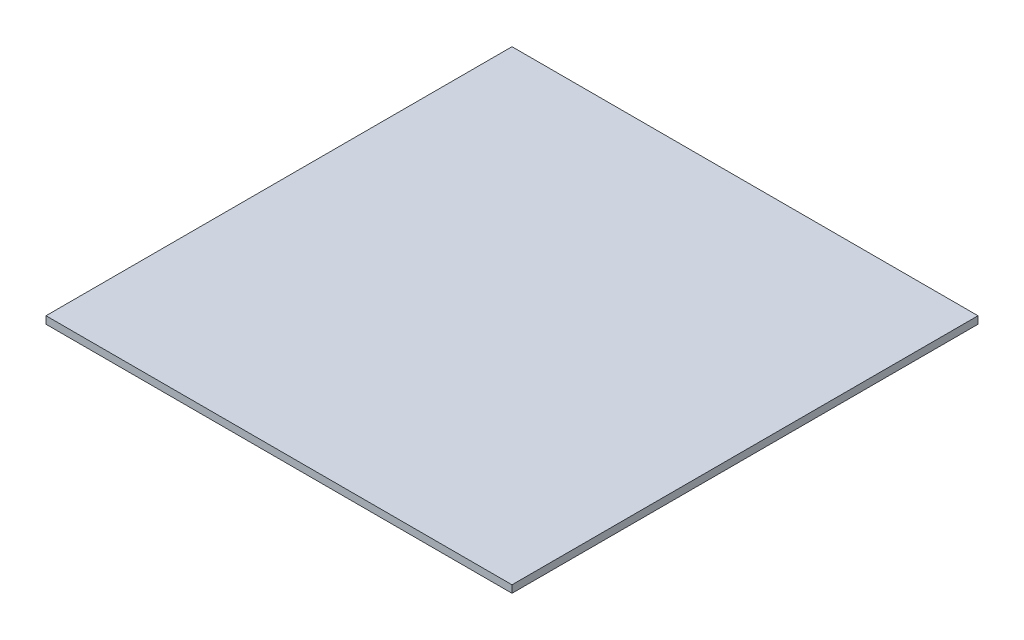
SolidWorks part; units mm, degrees
ref_plane "Front Plane" through (0, 0, 0) normal (0, 0, 1) x (1, 0, 0)
ref_plane "Top Plane" through (0, 0, 0) normal (0, 1, 0) x (1, 0, 0)
ref_plane "Right Plane" through (0, 0, 0) normal (1, 0, 0) x (0, 0, -1)
sketch "Sketch1" plane through (0, 0, 0) normal (0, 1, 0) x (1, 0, 0)
  line L1 (-100, -100) -> (100, -100)
  line L2 (-100, -100) -> (-100, 100)
  line L3 (-100, 100) -> (100, 100)
  line L4 (100, -100) -> (100, 100)
  line L5 (-100, -100) -> (100, 100) construction
  line L6 (-100, 100) -> (100, -100) construction
  point P0 (0, 0)
  dimension "D1" = 200
  dimension "D2" = 200
extrude "Boss-Extrude1" add sketch "Sketch1" along normal blind 3.175
